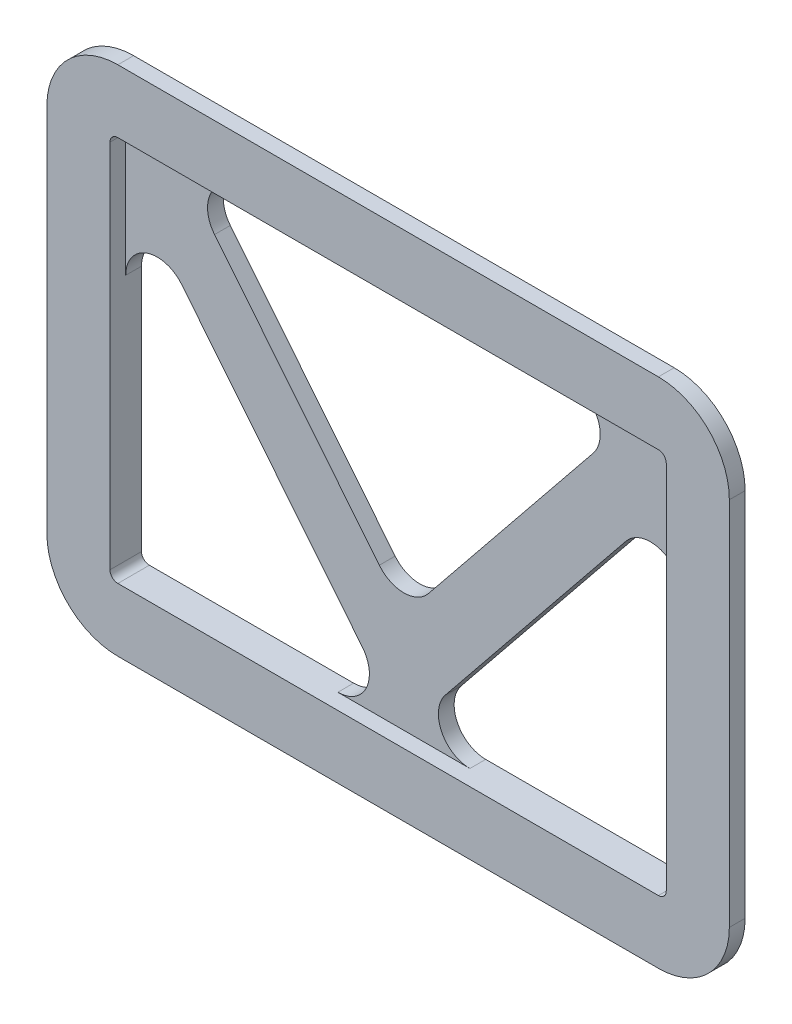
SolidWorks part; units mm, degrees
ref_plane "Front Plane" through (0, 0, 0) normal (0, 0, 1) x (1, 0, 0)
ref_plane "Top Plane" through (0, 0, 0) normal (0, 1, 0) x (1, 0, 0)
ref_plane "Right Plane" through (0, 0, 0) normal (1, 0, 0) x (0, 0, -1)
sketch "Sketch1" plane through (0, 0, 0) normal (0, 0, 1) x (1, 0, 0)
  line L0 (-25, 0) -> (-25, 234.8131)
  line L1 (0, -25) -> (342.7376, -25)
  line L2 (367.7376, 234.8131) -> (367.7376, 0)
  line L3 (0, 259.8131) -> (342.7376, 259.8131)
  line L4 (-5, 0) -> (-5, 156.7175)
  line L5 (66.8706, 239.8131) -> (275.867, 239.8131)
  line L6 (347.7376, 156.7175) -> (347.7376, 0)
  line L7 (213.2393, -5) -> (342.7376, -5)
  line L8 (51.3136, 207.2441) -> (155.8118, 77.9039)
  line L9 (186.9258, 77.9039) -> (291.424, 207.2441)
  line L10 (30.557, 169.2865) -> (145.0552, 27.569)
  line L11 (197.6824, 27.569) -> (312.1806, 169.2865)
  line L12 (0, 239.8131) -> (342.7376, 239.8131) construction
  line L13 (-5, 0) -> (-5, 234.8131) construction
  line L14 (347.7376, 234.8131) -> (347.7376, 0) construction
  line L15 (0, -5) -> (342.7376, -5) construction
  line L16 (129.4982, -5) -> (0, -5)
  arc A0 (-25, 0) -> (0, -25) centre (0, 0) ccw
  arc A1 (342.7376, -25) -> (367.7376, 0) centre (342.7376, 0) ccw
  arc A2 (367.7376, 234.8131) -> (342.7376, 259.8131) centre (342.7376, 234.8131) ccw
  arc A3 (0, 259.8131) -> (-25, 234.8131) centre (0, 234.8131) ccw
  arc A4 (0, 239.8131) -> (-5, 234.8131) centre (0, 234.8131) ccw
  arc A5 (347.7376, 234.8131) -> (342.7376, 239.8131) centre (342.7376, 234.8131) ccw
  arc A6 (342.7376, -5) -> (347.7376, 0) centre (342.7376, 0) ccw
  arc A7 (-5, 0) -> (0, -5) centre (0, 0) ccw
  arc A8 (51.3136, 207.2441) -> (66.8706, 239.8131) centre (66.8706, 219.8131) cw
  arc A9 (-5, 156.7175) -> (30.557, 169.2865) centre (15, 156.7175) cw
  arc A10 (155.8118, 77.9039) -> (186.9258, 77.9039) centre (171.3688, 90.4729) ccw
  arc A11 (275.867, 239.8131) -> (291.424, 207.2441) centre (275.867, 219.8131) cw
  arc A12 (347.7376, 156.7175) -> (312.1806, 169.2865) centre (327.7376, 156.7175) ccw
  arc A13 (213.2393, -5) -> (197.6824, 27.569) centre (213.2393, 15) cw
  arc A14 (145.0552, 27.569) -> (129.4982, -5) centre (129.4982, 15) cw
  dimension "D5" = 20
  dimension "D4" = 20
  dimension "D2" = 40
  dimension "D3" = 40
  dimension "D1" = 20
extrude "Boss-Extrude1" add sketch "Sketch1" along normal blind 10
sketch "Sketch2" plane through (0, 0, 10) normal (0, 0, 1) x (1, 0, 0)
  line L0 (342.7376, 239.8131) -> (0, 239.8131)
  line L1 (-5, 234.8131) -> (-5, 0)
  line L2 (0, -5) -> (342.7376, -5)
  line L3 (347.7376, 0) -> (347.7376, 234.8131)
  line L12 (342.7376, 279.8131) -> (0, 279.8131)
  line L13 (-45, 234.8131) -> (-45, 0)
  line L14 (0, -45) -> (342.7376, -45)
  line L15 (387.7376, 0) -> (387.7376, 234.8131)
  arc A0 (0, 239.8131) -> (-5, 234.8131) centre (0, 234.8131) ccw
  arc A1 (-5, 0) -> (0, -5) centre (0, 0) ccw
  arc A2 (342.7376, -5) -> (347.7376, 0) centre (342.7376, 0) ccw
  arc A3 (347.7376, 234.8131) -> (342.7376, 239.8131) centre (342.7376, 234.8131) ccw
  arc A12 (0, 279.8131) -> (-45, 234.8131) centre (0, 234.8131) ccw
  arc A13 (-45, 0) -> (0, -45) centre (0, 0) ccw
  arc A14 (342.7376, -45) -> (387.7376, 0) centre (342.7376, 0) ccw
  arc A15 (387.7376, 234.8131) -> (342.7376, 279.8131) centre (342.7376, 234.8131) ccw
  dimension "D1" = 40
extrude "Boss-Extrude2" add sketch "Sketch2" along normal blind 10
